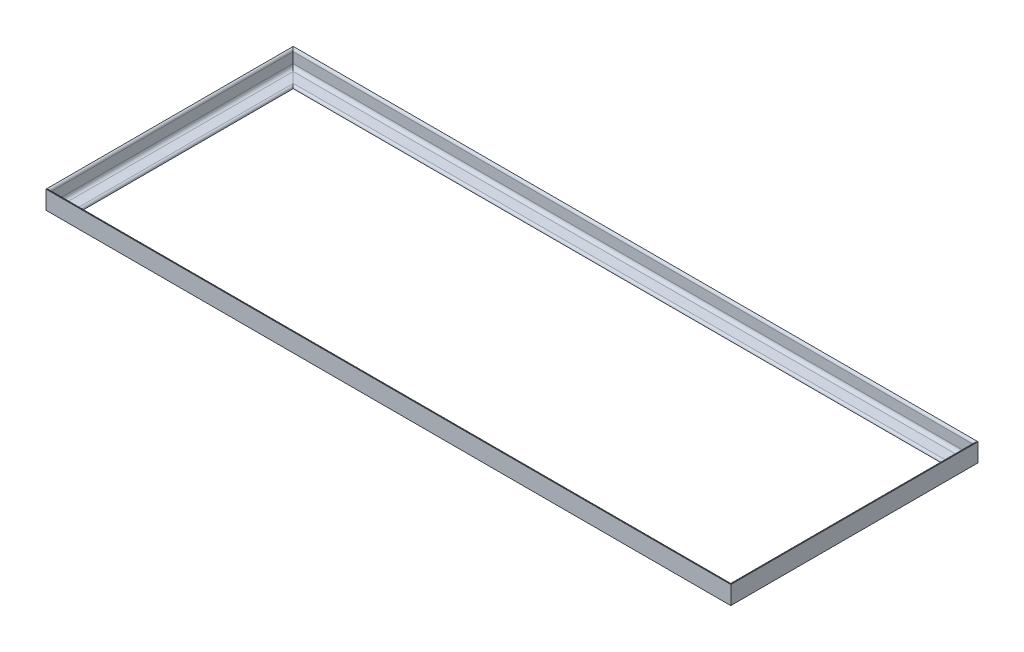
SolidWorks part; units mm, degrees
ref_plane "Alzado" through (0, 0, 0) normal (0, 0, 1) x (1, 0, 0)
ref_plane "Planta" through (0, 0, 0) normal (0, 1, 0) x (1, 0, 0)
ref_plane "Vista lateral" through (0, 0, 0) normal (1, 0, 0) x (0, 0, -1)
sketch "Croquis1" plane through (0, 0, 0) normal (0, 1, 0) x (1, 0, 0)
  line L1 (-475, 171.5) -> (475, 171.5)
  line L2 (-475, 171.5) -> (-475, -171.5)
  line L3 (-475, -171.5) -> (475, -171.5)
  line L4 (475, 171.5) -> (475, -171.5)
  line L5 (-475, 171.5) -> (475, -171.5) construction
  line L6 (-475, -171.5) -> (475, 171.5) construction
  point P0 (0, 0)
  dimension "D1" = 950
  dimension "D2" = 343
other "Hierro angular 1 X 1 X 0.125(1)"
ref_plane "Plano1" through (-475, 0, -171.5) normal (0, 0, 1) x (1, 0, 0)
sketch "Sketch1" plane through (-475, 0, -171.5) normal (0, 0, 1) x (1, 0, 0)
  line L0 (0, 0) -> (0, 25.4)
  line L1 (0, 25.4) -> (0.0051, 25.4)
  line L2 (3.175, 22.2301) -> (3.175, 7.9375)
  line L3 (7.9375, 3.175) -> (22.2301, 3.175)
  line L4 (25.4, 0.0051) -> (25.4, 0)
  line L5 (25.4, 0) -> (0, 0)
  arc A0 (25.4, 0.0051) -> (22.2301, 3.175) centre (22.2301, 0.0051) ccw
  arc A1 (0.0051, 25.4) -> (3.175, 22.2301) centre (0.0051, 22.2301) cw
  arc A2 (7.9375, 3.175) -> (3.175, 7.9375) centre (7.9375, 7.9375) cw
  point P10 (12.7, 0)
  point P14 (0, 12.7)
  point P15 (3.175, 12.7)
  point P16 (12.7, 3.175)
  point P17 (3.175, 25.4)
  point P18 (25.4, 3.175)
  point P19 (0, 0)
  dimension "D2" = 0.0051
  dimension "Radius_1" = 4.7625
  dimension "D1" = 3.175
  dimension "H_leg" = 25.4
